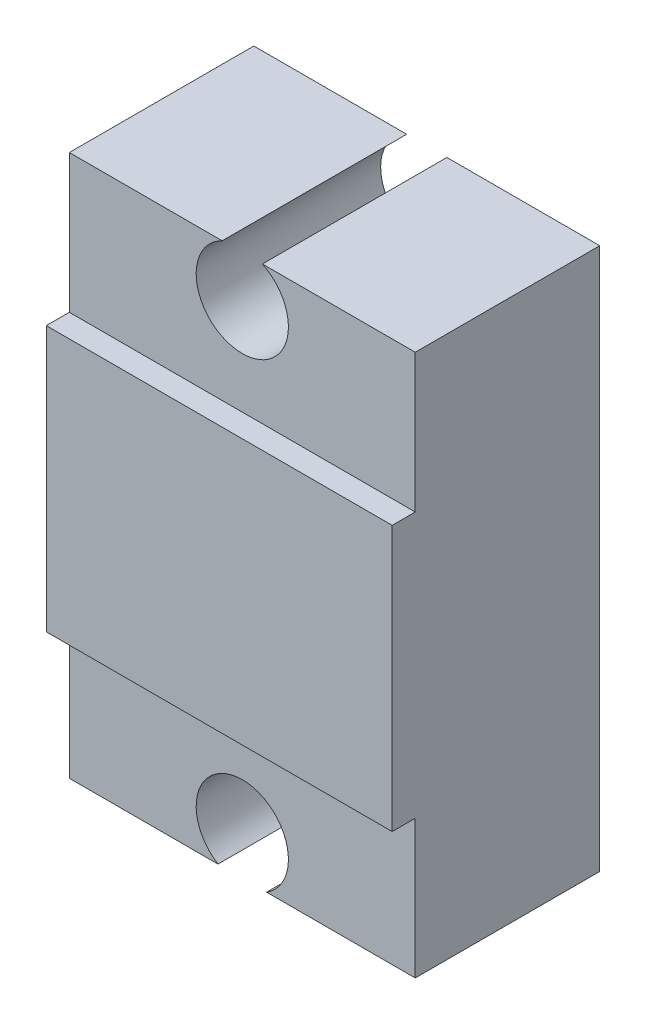
SolidWorks part; units mm, degrees
ref_plane "Front Plane" through (0, 0, 0) normal (0, 0, 1) x (1, 0, 0)
ref_plane "Top Plane" through (0, 0, 0) normal (0, 1, 0) x (1, 0, 0)
ref_plane "Right Plane" through (0, 0, 0) normal (1, 0, 0) x (0, 0, -1)
sketch "Sketch1" plane through (0, 0, 0) normal (0, 0, 1) x (1, 0, 0)
  line L1 (-7.8619, 10.0164) -> (11.1881, 10.0164)
  line L2 (-7.8619, 10.0164) -> (-7.8619, -19.8286)
  line L3 (-7.8619, -19.8286) -> (11.1881, -19.8286)
  line L4 (11.1881, 10.0164) -> (11.1881, -19.8286)
  dimension "D1" = 19.05
  dimension "D2" = 29.845
extrude "Boss-Extrude1" add sketch "Sketch1" along normal blind 11.43
sketch "Sketch2" plane through (0, 0, 11.43) normal (0, 0, 1) x (1, 0, 0)
  line L0 (-7.8619, 10.0164) -> (-7.8619, -19.8286) construction
  line L1 (-7.8619, -19.8286) -> (11.1881, -19.8286) construction
  circle A0 centre (1.6631, 7.7304) radius 2.54
  circle A1 centre (1.6631, -17.6696) radius 2.54
  point P4 (0, 0)
  point P5 (0, 0)
  dimension "D1" = 5.08
  dimension "D2" = 25.4
  dimension "D3" = 9.525
  dimension "D4" = 2.159
extrude "Cut-Extrude1" cut sketch "Sketch2" against normal blind 11.43
sketch "Sketch3" plane through (0, 0, 11.43) normal (0, 0, 1) x (1, 0, 0)
  line L0 (-7.8619, 10.0164) -> (-7.8619, -19.8286) construction
  line L1 (-7.8619, 2.3964) -> (11.1881, 2.3964)
  line L2 (-7.8619, 2.3964) -> (-7.8619, 10.0164)
  line L3 (-7.8619, 10.0164) -> (11.1881, 10.0164)
  line L4 (11.1881, 2.3964) -> (11.1881, 10.0164)
  line L5 (11.1881, -19.8286) -> (11.1881, 10.0164) construction
  line L6 (0.5559, 10.0164) -> (-7.8619, 10.0164) construction
  line L7 (-7.8619, -19.8286) -> (11.1881, -19.8286)
  line L8 (-7.8619, -19.8286) -> (-7.8619, -12.2086)
  line L9 (-7.8619, -12.2086) -> (11.1881, -12.2086)
  line L10 (11.1881, -19.8286) -> (11.1881, -12.2086)
  dimension "D1" = 7.62
extrude "Cut-Extrude2" cut sketch "Sketch3" against normal blind 1.27
